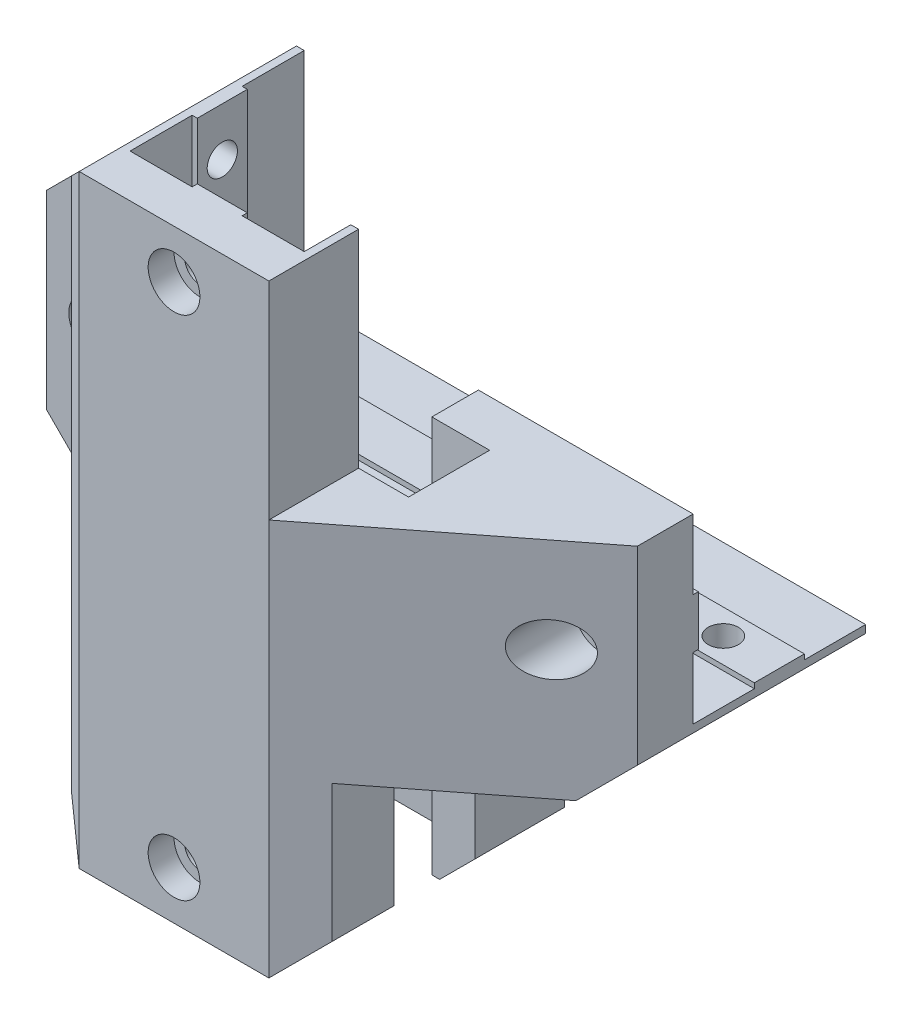
SolidWorks part; units mm, degrees
ref_plane "前视基准面" through (0, 0, 0) normal (0, 0, 1) x (1, 0, 0)
ref_plane "上视基准面" through (0, 0, 0) normal (0, 1, 0) x (1, 0, 0)
ref_plane "右视基准面" through (0, 0, 0) normal (1, 0, 0) x (0, 0, -1)
sketch "草图1" plane through (0, 0, 0) normal (0, 0, 1) x (1, 0, 0)
  line L0 (-34.8554, 14.0448) -> (-10.8554, 38.0448)
  line L1 (-10.8554, 38.0448) -> (11.1446, 38.0448)
  line L2 (0.1446, 20.1596) -> (0.1446, -5.7587) construction
  line L3 (-34.8554, 14.0448) -> (-34.8554, -7.9552)
  line L4 (1.9172, 3.0448) -> (47933.0111, 3.0448) construction
  line L5 (-10.8554, -31.9552) -> (11.1446, -31.9552)
  line L6 (-34.8554, -7.9552) -> (-10.8554, -31.9552)
  line L7 (35.1446, -7.9552) -> (11.1446, -31.9552)
  line L8 (35.1446, 14.0448) -> (35.1446, -7.9552)
  line L9 (35.1446, 14.0448) -> (11.1446, 38.0448)
  point P9 (-34.8554, 3.0448)
  point P12 (0.1446, 38.0448)
  point P13 (0.1446, -31.9552)
  point P15 (35.1446, 3.0448)
  dimension "D1" = 22
  dimension "D2" = 22
  dimension "D3" = 35
  dimension "D4" = 35
extrude "凸台-拉伸1" add sketch "草图1" along normal blind 22
sketch "草图2" plane through (0, 38.0448, 0) normal (0, 1, 0) x (1, 0, 0)
  line L0 (0.1446, -22) -> (0.1446, 49978) construction
  line L1 (11.1446, 0) -> (-10.8554, 0) construction
  line L2 (-10.8554, -11) -> (49989.1446, -11) construction
  line L3 (-10.8554, -22) -> (-10.8554, 0) construction
  line L4 (11.1446, -22) -> (11.1446, 0) construction
  line L5 (11.1446, -22) -> (-10.8554, -22) construction
  line L6 (-9.9554, -10.1) -> (49990.0446, -10.1) construction
  line L7 (-9.9554, 0) -> (10.2446, 0)
  line L8 (-9.9554, 0) -> (-9.9554, -20.2)
  line L9 (-9.9554, -20.2) -> (10.2446, -20.2)
  line L10 (10.2446, 0) -> (10.2446, -5.4)
  line L12 (10.2446, -14.8) -> (16.9446, -14.8)
  line L13 (-9.9554, -7.2) -> (-9.3554, -7.2)
  line L14 (10.2446, -5.4) -> (16.9446, -5.4)
  line L15 (16.9446, -14.8) -> (16.9446, -5.4)
  line L16 (10.2446, -14.8) -> (10.2446, -20.2)
  line L17 (-9.9554, -7.2) -> (-9.9554, -13)
  line L18 (-9.9554, -13) -> (-9.3554, -13)
  line L19 (-9.3554, -7.2) -> (-9.3554, -13)
  line L20 (-2.7554, -20.2) -> (3.0446, -20.2)
  line L21 (-2.7554, -20.2) -> (-2.7554, -19.6)
  line L22 (-2.7554, -19.6) -> (3.0446, -19.6)
  line L23 (3.0446, -20.2) -> (3.0446, -19.6)
  point P10 (-10.8554, -11)
  point P13 (11.1446, -11)
  point P18 (0.1446, -22)
  point P21 (-9.9554, -10.1)
  dimension "D1" = 20.2
  dimension "D2" = 20.2
  dimension "D3" = 9.4
  dimension "D4" = 6.7
  dimension "D5" = 5.8
  dimension "D6" = 5.8
  dimension "D7" = 0.6
  dimension "D8" = 0.6
extrude "切除-拉伸2" cut sketch "草图2" against normal through all contours L23 L9 L16 L12 L7 L14 L10 L4 L8 L13 L19 L18 L21 L22 | L12 L15 L14 L7
sketch "草图3" plane through (0, 0, 0) normal (0, 0, -1) x (-1, 0, 0)
  line L0 (34.8554, 3.0448) -> (-49965.1446, 3.0448) construction
  line L1 (34.8554, 14.0448) -> (34.8554, -7.9552) construction
  line L2 (9.9554, -31.9552) -> (9.9554, 38.0448) construction
  line L3 (34.8554, 5.9448) -> (9.9554, 5.9448)
  line L4 (34.8554, 5.9448) -> (34.8554, 0.1448)
  line L5 (34.8554, 0.1448) -> (9.9554, 0.1448)
  line L6 (9.9554, 5.9448) -> (9.9554, 0.1448)
  line L7 (-35.1446, -7.9552) -> (-35.1446, 14.0448) construction
  line L8 (-35.1446, 5.9448) -> (-10.2446, 5.9448)
  line L9 (-35.1446, 5.9448) -> (-35.1446, 0.1448)
  line L10 (-35.1446, 0.1448) -> (-10.2446, 0.1448)
  line L11 (-10.2446, 5.9448) -> (-10.2446, 0.1448)
  line L12 (-10.2446, -31.9552) -> (-10.2446, 38.0448) construction
  point P4 (34.8554, 3.0448)
  dimension "D1" = 5.8
extrude "凸台-拉伸2" add sketch "草图3" along normal blind 0.6
sketch "草图4" plane through (0, 0, 0) normal (0, 0, -1) x (-1, 0, 0)
  line L0 (-35.1446, 14.0448) -> (-11.1446, 38.0448)
  line L1 (-11.1446, 38.0448) -> (-11.1446, 14.0448)
  line L2 (-11.1446, 14.0448) -> (-35.1446, 14.0448)
extrude "切除-拉伸3" cut sketch "草图4" against normal through all
sketch "草图5" plane through (0, 0, 0) normal (0, 0, -1) x (-1, 0, 0)
  line L0 (-11.1446, -31.9552) -> (10.8554, -31.9552)
  line L1 (34.8554, -7.9552) -> (10.8554, -31.9552) construction
  line L2 (10.8554, -31.9552) -> (34.8554, -7.9552)
  line L3 (34.8554, -7.9552) -> (34.8554, -7.0552)
  line L4 (34.8554, 0.1448) -> (34.8554, -7.9552) construction
  line L5 (34.8554, -7.0552) -> (-35.1446, -7.0552)
  line L6 (-35.1446, -7.9552) -> (-35.1446, 0.1448) construction
  line L7 (-35.1446, -7.0552) -> (-35.1446, -7.9552)
  line L8 (-35.1446, -7.9552) -> (-11.1446, -31.9552)
  dimension "D1" = 0.9
extrude "凸台-拉伸3" add sketch "草图5" along normal blind 20
sketch "草图6" plane through (0, 0, 0) normal (0, 0, -1) x (-1, 0, 0)
  line L0 (14.9554, 33.9448) -> (30.8554, 18.0448)
  line L1 (10.8554, 38.0448) -> (34.8554, 14.0448) construction
  line L2 (14.9554, 33.9448) -> (14.9554, 18.0448)
  line L3 (14.9554, 18.0448) -> (30.8554, 18.0448)
  line L4 (9.9554, 5.9448) -> (9.9554, 38.0448) construction
  line L5 (-35.1446, 14.0448) -> (-11.1446, 14.0448) construction
  line L6 (34.8554, 3.0448) -> (-49965.1446, 3.0448) construction
  line L7 (34.8554, 14.0448) -> (34.8554, -7.9552) construction
  line L8 (-35.1446, -7.9552) -> (-35.1446, 14.0448) construction
  line L9 (-0.1446, -31.9552) -> (-0.1446, 49968.0448) construction
  line L10 (10.8554, -31.9552) -> (-11.1446, -31.9552) construction
  line L11 (-11.1446, 38.0448) -> (10.8554, 38.0448) construction
  line L12 (14.9554, -11.9552) -> (30.8554, -11.9552)
  line L13 (14.9554, -27.8552) -> (30.8554, -11.9552)
  line L14 (14.9554, -27.8552) -> (14.9554, -11.9552)
  line L15 (-15.2446, -11.9552) -> (-31.1446, -11.9552)
  line L16 (-15.2446, -27.8552) -> (-31.1446, -11.9552)
  line L17 (-15.2446, -27.8552) -> (-15.2446, -11.9552)
  point P13 (34.8554, 3.0448)
  point P16 (-35.1446, 3.0448)
  point P21 (-0.1446, -31.9552)
  point P24 (-0.1446, 38.0448)
  dimension "D1" = 5
  dimension "D2" = 4
extrude "切除-拉伸4" cut sketch "草图6" against normal through all and the other way through all
sketch "草图7" plane through (0, 18.0448, 0) normal (0, 1, 0) x (1, 0, 0)
  line L0 (-34.8554, -22) -> (-34.8554, 0) construction
  line L1 (-34.8554, -5) -> (-14.9554, -5)
  line L2 (-34.8554, -5) -> (-34.8554, -22)
  line L3 (-34.8554, -22) -> (-14.9554, -22)
  line L4 (-14.9554, -5) -> (-14.9554, -22)
  line L5 (0.1446, -22) -> (0.1446, 20) construction
  line L6 (11.1446, -22) -> (-10.8554, -22) construction
  line L7 (-34.8554, 20) -> (35.1446, 20) construction
  line L8 (35.1446, -5) -> (35.1446, -22)
  line L9 (35.1446, -22) -> (15.2446, -22)
  line L10 (15.2446, -5) -> (15.2446, -22)
  line L11 (35.1446, -5) -> (15.2446, -5)
  line L12 (-34.8554, 0) -> (-9.9554, 0) construction
  point P17 (-22.4054, 0)
  dimension "D1" = 5
extrude "切除-拉伸5" cut sketch "草图7" against normal through all
sketch "草图8" plane through (-14.9554, 0, 0) normal (-1, 0, 0) x (0, 0, 1)
  line L0 (5, -11.9552) -> (-20, -11.9552) construction
  line L1 (-20, -31.9552) -> (-5, -31.9552)
  line L2 (-20, -31.9552) -> (-20, -11.9552)
  line L3 (-20, -11.9552) -> (-5, -11.9552)
  line L4 (-5, -31.9552) -> (-5, -11.9552)
  line L5 (0, 0.1448) -> (0, -7.0552) construction
  dimension "D1" = 5
extrude "切除-拉伸6" cut sketch "草图8" against normal through all
sketch "草图9" plane through (0, 0, -0.6) normal (0, 0, -1) x (-1, 0, 0)
  line L0 (-35.1446, 3.0448) -> (34.8554, 3.0448) construction
  line L1 (-35.1446, 5.9448) -> (-35.1446, 0.1448) construction
  line L2 (34.8554, 0.1448) -> (34.8554, 5.9448) construction
  line L3 (-0.1446, 37.4314) -> (-0.1446, 17.0307) construction
  line L5 (2.7554, 38.0448) -> (-3.0446, 38.0448) construction
  circle A0 centre (-29.5446, 3.0448) radius 1.75
  circle A1 centre (29.2554, 3.0448) radius 1.75
  circle A2 centre (-0.1446, 32.4448) radius 1.75
  circle A3 centre (-0.1446, -26.3552) radius 1.75
  dimension "D1" = 3.5
  dimension "D3" = 3.5
  dimension "D2" = 5.6
  dimension "D4" = 5.6
extrude "切除-拉伸7" cut sketch "草图9" against normal through all and the other way through all
sketch "草图10" plane through (-9.3554, 0, 0) normal (1, 0, 0) x (0, 0, -1)
  line L0 (-10.1, 38.0448) -> (-10.1, -49961.9552) construction
  line L1 (-7.2, 38.0448) -> (-13, 38.0448) construction
  line L2 (-7.2, -31.9552) -> (-13, -31.9552) construction
  line L3 (-13, 3.0448) -> (9.0232, 3.0448) construction
  line L4 (-13, -31.9552) -> (-13, 38.0448) construction
  circle A0 centre (-10.1, 32.4448) radius 1.75
  circle A1 centre (-10.1, -26.3552) radius 1.75
  circle A2 centre (-10.1, 3.0448) radius 1.75
  point P4 (-10.1, 38.0448)
  point P7 (-10.1, -31.9552)
  dimension "D1" = 3.5
  dimension "D3" = 3.5
  dimension "D5" = 3.5
  dimension "D2" = 5.6
  dimension "D4" = 5.6
extrude "切除-拉伸8" cut sketch "草图10" against normal through all
sketch "草图11" plane through (0, 0, 0) normal (0, 0, -1) x (-1, 0, 0)
  line L0 (-10.2446, 5.9448) -> (-10.2446, 38.0448) construction
  line L1 (-11.1446, 38.0448) -> (-10.2446, 38.0448)
  line L2 (-11.1446, 38.0448) -> (-11.1446, 14.0448)
  line L3 (-11.1446, 14.0448) -> (-10.2446, 14.0448)
  line L4 (-10.2446, 38.0448) -> (-10.2446, 14.0448)
extrude "切除-拉伸9" cut sketch "草图11" against normal blind 10
sketch "草图12" plane through (0, 38.0448, 0) normal (0, 1, 0) x (1, 0, 0)
  line L0 (0.1446, -22.5047) -> (0.1446, -27.6493) construction
  line L2 (-14.9554, -22) -> (-10.8554, -25.2)
  line L3 (-10.8554, -25.2) -> (11.1446, -25.2)
  line L4 (-14.9554, -22) -> (15.2446, -22)
  line L5 (15.2446, -22) -> (11.1446, -25.2)
  line L6 (-9.9554, -20.2) -> (-2.7554, -20.2) construction
  point P8 (0.1446, -22)
  point P9 (0.1446, -25.2)
  dimension "D1" = 5
extrude "凸台-拉伸4" add sketch "草图12" against normal up to vertex (70 mm away)
sketch "草图13" plane through (0, 0, 22) normal (0, 0, -1) x (-1, 0, 0)
  line L0 (10.8554, 38.0448) -> (14.9554, 38.0448)
  line L1 (-15.2446, 38.0448) -> (-11.1446, 38.0448)
  line L2 (-15.2446, 38.0448) -> (-15.2446, 14.0448)
  line L3 (-15.2446, 14.0448) -> (-11.1446, 14.0448)
  line L4 (-11.1446, 38.0448) -> (-11.1446, 14.0448)
  line L5 (14.9554, 38.0448) -> (14.9554, 33.9448)
  line L6 (14.9554, 33.9448) -> (10.8554, 38.0448)
  line L7 (14.9554, -27.8552) -> (14.9554, -31.9552)
  line L8 (14.9554, -31.9552) -> (14.9554, -27.8552) construction
  line L9 (14.9554, -31.9552) -> (10.8554, -31.9552)
  line L10 (10.8554, -31.9552) -> (14.9554, -27.8552)
  line L11 (14.9554, -27.8552) -> (14.964, -27.9192)
  line L12 (-15.2446, -31.9552) -> (-11.1446, -31.9552)
  line L13 (-11.1446, -31.9552) -> (-15.2446, -27.8552)
  line L14 (-15.2446, -27.8552) -> (-15.2446, -31.9552)
extrude "切除-拉伸10" cut sketch "草图13" against normal through all contours L6 L5 L0 | L10 L9 L7 | L13 L14 L12
sketch "草图14" plane through (0, 0, 19.6) normal (0, 0, -1) x (-1, 0, 0)
  circle A0 centre (-0.1446, 32.4448) radius 1.75
  circle A1 centre (-0.1446, -26.3552) radius 1.75
extrude "切除-拉伸11" cut sketch "草图14" against normal through all
sketch "草图15" plane through (-34.8554, 0, 0) normal (-1, 0, 0) x (0, 0, 1)
  line L0 (-20, -7.0552) -> (0, -7.0552) construction
  line L1 (-12.9, -7.0552) -> (-7.1, -7.0552)
  line L2 (-12.9, -7.0552) -> (-12.9, -6.4552)
  line L3 (-12.9, -6.4552) -> (-7.1, -6.4552)
  line L4 (-7.1, -7.0552) -> (-7.1, -6.4552)
  line L5 (-10, -7.0552) -> (-10, 49992.9448) construction
  line L6 (0, 0.1448) -> (0, -7.0552) construction
  dimension "D1" = 5.8
  dimension "D2" = 0.6
  dimension "D3" = 10
extrude "凸台-拉伸5" add sketch "草图15" against normal up to vertex (70 mm away)
sketch "草图16" plane through (0, -6.4552, 0) normal (0, 1, 0) x (1, 0, 0)
  line L0 (-34.8554, 10) -> (35.1446, 10) construction
  line L1 (-34.8554, 7.1) -> (-34.8554, 12.9) construction
  line L2 (35.1446, 7.1) -> (35.1446, 12.9) construction
  line L3 (0.1446, 20) -> (0.1446, -6.7462) construction
  line L4 (-34.8554, 20) -> (35.1446, 20) construction
  circle A0 centre (-28.3554, 10) radius 1.75
  circle A1 centre (28.6446, 10) radius 1.75
  circle A2 centre (0.1446, 10) radius 1.75
  dimension "D1" = 3.5
  dimension "D3" = 3.5
  dimension "D2" = 6.5
extrude "切除-拉伸12" cut sketch "草图16" against normal through all
sketch "草图17" plane through (0, 14.0448, 0) normal (0, 1, 0) x (1, 0, 0)
  line L0 (15.2446, -5) -> (15.2446, -22)
  line L1 (15.2446, -22) -> (35.1446, -6.4683)
  line L2 (35.1446, -6.4683) -> (35.1446, -5)
  line L3 (35.1446, -5) -> (15.2446, -5)
extrude "凸台-拉伸6" add sketch "草图17" against normal up to vertex
sketch "草图18" plane through (0, 0, 5) normal (0, 0, -1) x (-1, 0, 0)
  line L0 (-35.1446, -11.9552) -> (-35.1446, -7.9552)
  line L1 (-35.1446, -7.9552) -> (-31.1446, -11.9552)
  line L2 (-31.1446, -11.9552) -> (-35.1446, -11.9552)
  circle A0 centre (-29.5446, 3.0448) radius 1.75
extrude "切除-拉伸13" cut sketch "草图18" against normal through all
sketch "草图20" plane through (0, 0, 25.2) normal (0, 0, 1) x (1, 0, 0)
  circle A0 centre (0.1446, 32.4448) radius 3
  circle A1 centre (0.1446, -26.3552) radius 3
  dimension "D1" = 6
  dimension "D2" = 6
extrude "切除-拉伸17" cut sketch "草图20" against normal blind 3
sketch "草图21" plane through (0, 0, 25.2) normal (0, 0, 1) x (1, 0, 0)
  circle A0 centre (29.5446, 3.0448) radius 3
  dimension "D1" = 6
extrude "切除-拉伸18" cut sketch "草图21" against normal blind 20
sketch "草图22" plane through (-14.9554, 0, 0) normal (-1, 0, 0) x (0, 0, 1)
  circle A0 centre (10.1, 32.4448) radius 3
  circle A1 centre (10.1, 3.0448) radius 3
  circle A2 centre (10.1, -26.3552) radius 3
  dimension "D1" = 6
  dimension "D2" = 6
  dimension "D3" = 6
extrude "切除-拉伸19" cut sketch "草图22" against normal blind 3
sketch "草图23" plane through (0, -11.9552, 0) normal (0, -1, 0) x (1, 0, 0)
  circle A0 centre (-28.3554, -10) radius 3
  circle A1 centre (0.1446, -10) radius 3
  circle A2 centre (28.6446, -10) radius 3
  dimension "D1" = 6
  dimension "D2" = 6
  dimension "D3" = 6
extrude "切除-拉伸20" cut sketch "草图23" against normal blind 3
sketch "草图24" plane through (0, 0, -5) normal (0, 0, -1) x (-1, 0, 0)
  circle A0 centre (-0.1446, -26.3552) radius 3
  dimension "D1" = 6
extrude "切除-拉伸21" cut sketch "草图24" against normal blind 3
sketch "草图25" plane through (0, 0, 5) normal (0, 0, 1) x (1, 0, 0)
  circle A0 centre (-29.2554, 3.0448) radius 3
  dimension "D1" = 6
extrude "切除-拉伸22" cut sketch "草图25" against normal blind 3
sketch "草图26" plane through (0, 38.0448, 0) normal (0, 1, 0) x (1, 0, 0)
  line L1 (10.2446, -5.4) -> (15.2446, -5.4) construction
  line L2 (10.2446, -14.8) -> (16.9446, -14.8)
  line L3 (10.2446, -14.8) -> (10.2446, -5.4)
  line L4 (10.2446, -5.4) -> (16.9446, -5.4)
  line L5 (16.9446, -14.8) -> (16.9446, -5.4)
  dimension "D1" = 6.7
extrude "切除-拉伸23" cut sketch "草图26" against normal through all
